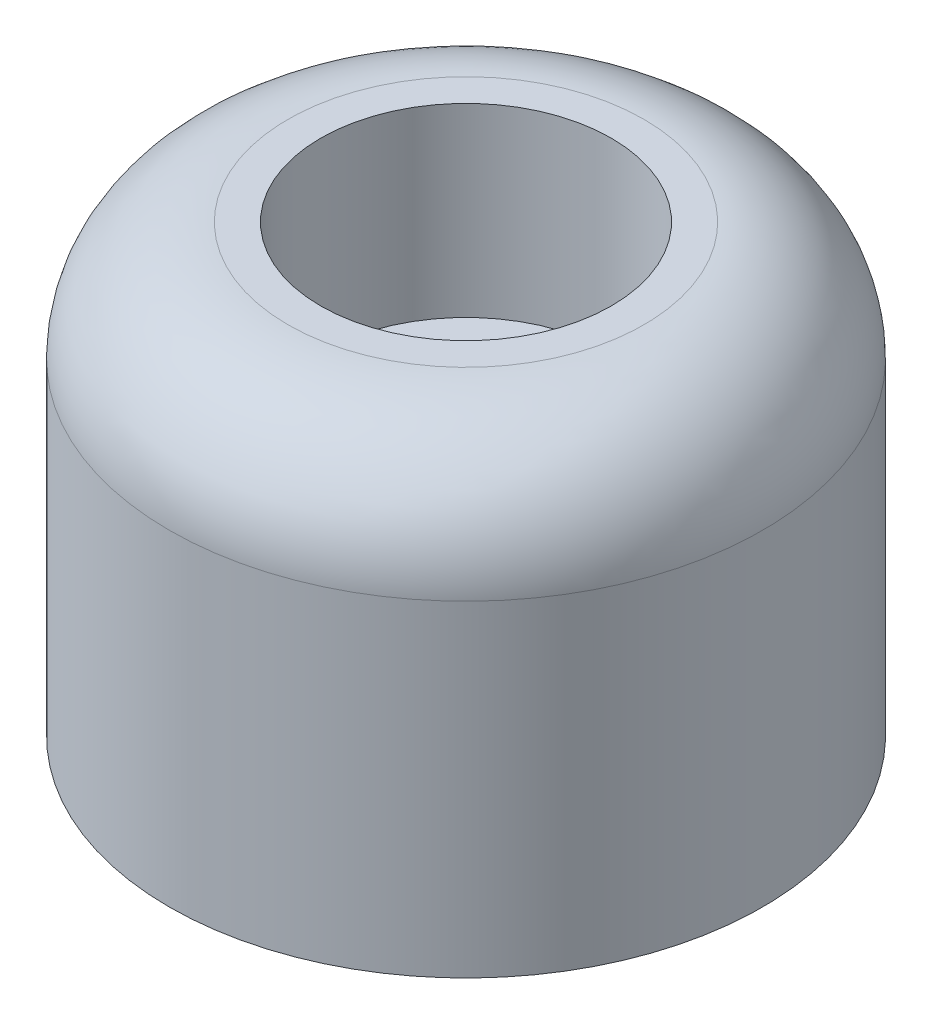
SolidWorks part; units mm, degrees
ref_plane "Front Plane" through (0, 0, 0) normal (0, 0, 1) x (1, 0, 0)
ref_plane "Top Plane" through (0, 0, 0) normal (0, 1, 0) x (1, 0, 0)
ref_plane "Right Plane" through (0, 0, 0) normal (1, 0, 0) x (0, 0, -1)
sketch "Croquis1" plane through (0, 0, 0) normal (0, 1, 0) x (1, 0, 0)
  circle A0 centre (0, 0) radius 12.7
  dimension "D1" = 25.4
extrude "Saliente-Extruir1" add sketch "Croquis1" along normal blind 19.05
hole_wizard "Refrentado para tornillo con cabeza hueca de 5/161" positions "Croquis4" profile "Croquis3" counterbore size "5/16" standard "Ansi Inch"
sketch "Croquis4" plane through (0, 19.05, 0) normal (0, 1, 0) x (1, 0, 0)
  point P0 (0, 0)
sketch "Croquis3" plane through (0, 19.05, 0) normal (1, 0, 0) x (0, 0, 1)
  line L0 (0, 0) -> (0, 22.2133)
  line L1 (0, 22.2133) -> (4.1021, 19.7485)
  line L2 (4.1021, 19.7485) -> (4.1021, 7.9375)
  line L3 (4.1021, 7.9375) -> (6.223, 7.9375)
  line L4 (6.223, 7.9375) -> (6.223, 0)
  line L5 (6.223, 0) -> (0, 0)
  line L10 (0, 22.2133) -> (-4.1021, 19.7485) construction
  line L11 (0, -6.35) -> (0, 107.95) construction
  dimension "Diámetro de taladro" = 8.2042
  dimension "Profundidad de taladro" = 19.7485
  dimension "Diámetro de refrentado" = 12.446
  dimension "Profundidad de refrentado" = 7.9375
  dimension "Ángulo de perforador" = 118
fillet "Redondeo1" radius 5.08 1 edges at (0, 19.05, 12.7)
